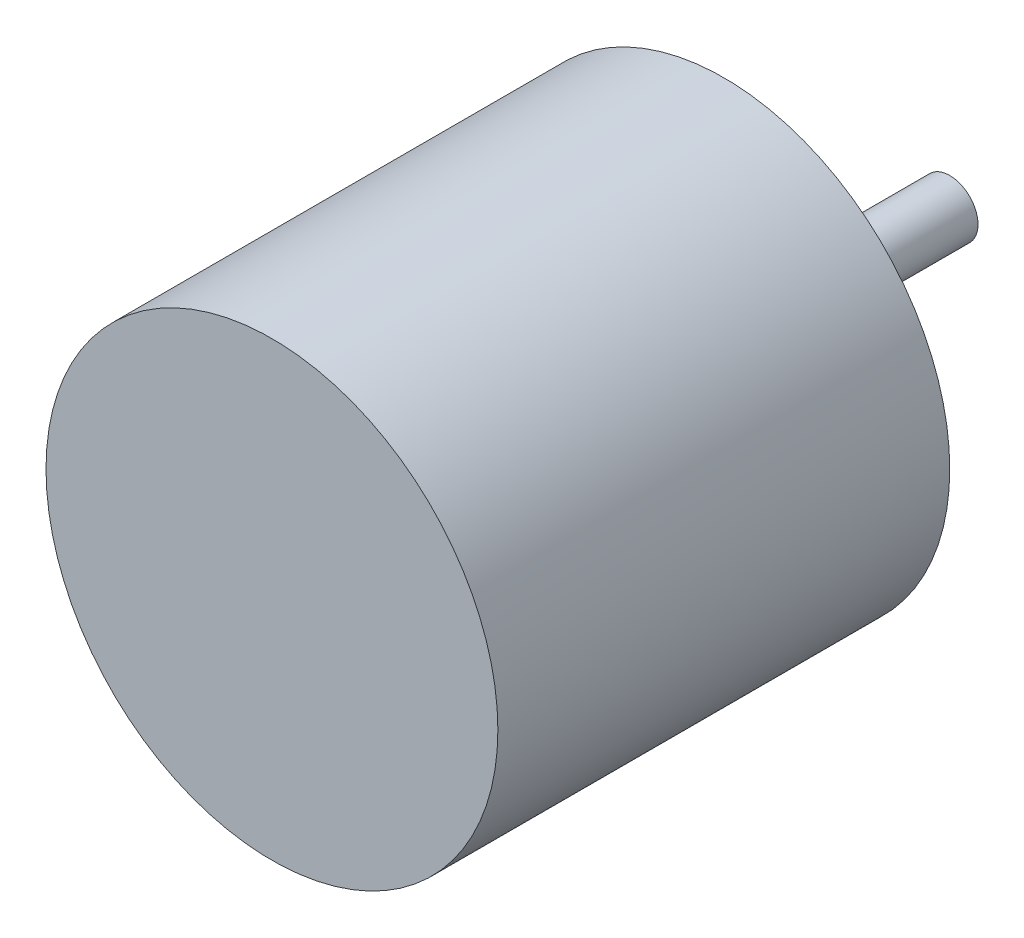
SolidWorks part; units mm, degrees
ref_plane "Front Plane" through (0, 0, 0) normal (0, 0, 1) x (1, 0, 0)
ref_plane "Top Plane" through (0, 0, 0) normal (0, 1, 0) x (1, 0, 0)
ref_plane "Right Plane" through (0, 0, 0) normal (1, 0, 0) x (0, 0, -1)
sketch "Sketch4" plane through (0, 0, 0) normal (0, 1, 0) x (1, 0, 0)
  line L0 (0, 0) -> (0, 60) construction
  line L1 (0, 60) -> (-2.5, 60)
  line L2 (-2.5, 60) -> (-2.5, 45)
  line L3 (-2.5, 45) -> (-10, 45)
  line L4 (-10, 45) -> (-10, 40)
  line L5 (-10, 40) -> (-20, 40)
  line L6 (-20, 40) -> (-20, 0)
  line L7 (-20, 0) -> (0, 0)
  line L8 (0, 0) -> (0, 60)
  dimension "D1" = 20
  dimension "D2" = 40
  dimension "D3" = 15
  dimension "D4" = 5
  dimension "D5" = 2.5
  dimension "D6" = 10
revolve "Revolve1" add sketch "Sketch4" angle 360 about L0
sketch "Sketch5" plane through (0, 0, 0) normal (0, 1, 0) x (1, 0, 0)
  line L0 (0, 0) -> (0, 107.8608) construction
